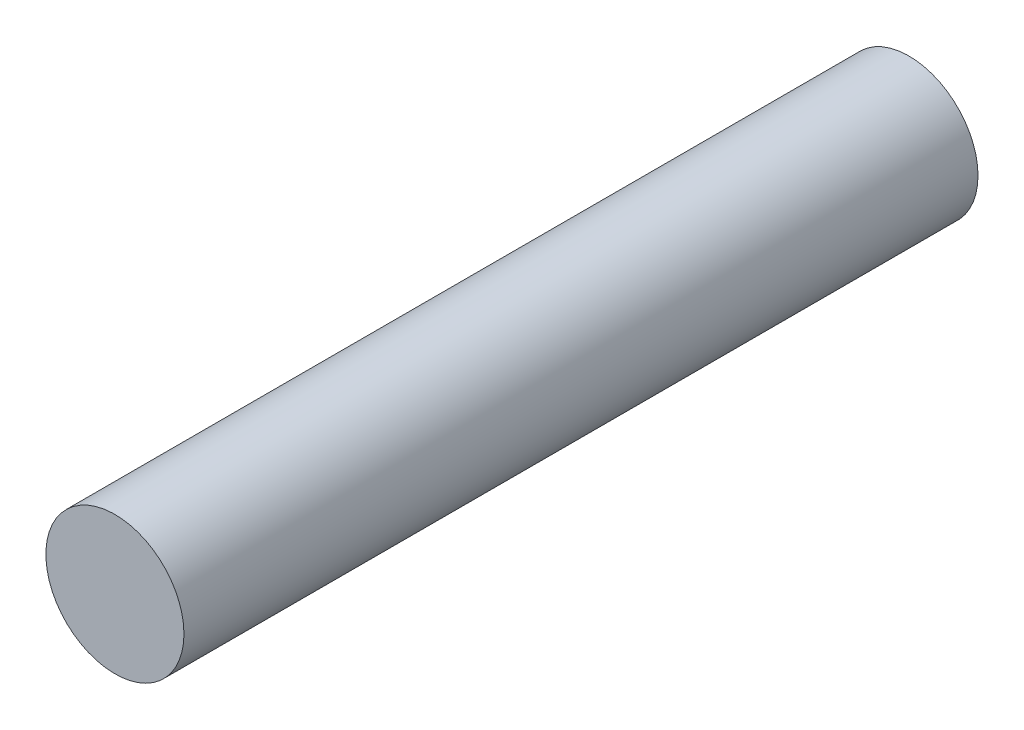
SolidWorks part; units mm, degrees
material "Oak"
ref_plane "Front Plane" through (0, 0, 0) normal (0, 0, 1) x (1, 0, 0)
ref_plane "Top Plane" through (0, 0, 0) normal (0, 1, 0) x (1, 0, 0)
ref_plane "Right Plane" through (0, 0, 0) normal (1, 0, 0) x (0, 0, -1)
sketch "Sketch1" plane through (0, 0, 0) normal (0, 0, 1) x (1, 0, 0)
  circle A0 centre (0, 0) radius 10
  dimension "D1" = 20
extrude "Boss-Extrude1" add sketch "Sketch1" along normal blind 115
